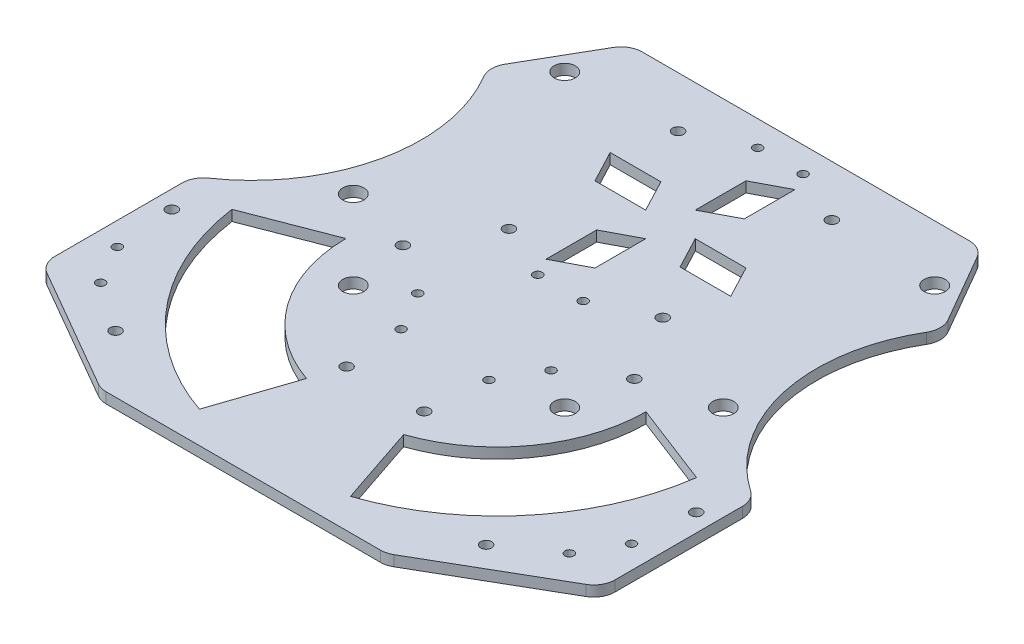
SolidWorks part; units mm, degrees
ref_plane "前视基准面" through (0, 0, 0) normal (0, 0, 1) x (1, 0, 0)
ref_plane "上视基准面" through (0, 0, 0) normal (0, 1, 0) x (1, 0, 0)
ref_plane "右视基准面" through (0, 0, 0) normal (1, 0, 0) x (0, 0, -1)
sketch "草图1" plane through (0, 0, 0) normal (0, 1, 0) x (1, 0, 0)
  line L0 (0, 0) -> (0, 50000) construction
  line L1 (0, 0) -> (-43301.2702, 25000) construction
  line L2 (-0.5416, -0.3127) -> (43300.7286, 24999.6873) construction
  line L3 (-34.641, 150) -> (-147.2243, -45)
  line L4 (34.641, 150) -> (147.2243, -45)
  line L5 (112.5833, -105) -> (-112.5833, -105)
  arc A0 (34.641, 150) -> (-34.641, 150) centre (0, 130) ccw
  arc A1 (-147.2243, -45) -> (-112.5833, -105) centre (-112.5833, -65) ccw
  arc A3 (147.2243, -45) -> (112.5833, -105) centre (112.5833, -65) cw
  dimension "D6" = 80
  dimension "D1" = 60
  dimension "D2" = 60
  dimension "D3" = 130
  dimension "D5" = 130
extrude "凸台-拉伸1" add sketch "草图1" along normal blind 5
sketch "草图2" plane through (0, 5, 0) normal (0, 1, 0) x (1, 0, 0)
  line L0 (0, 0) -> (0, 50000) construction
  line L1 (-10.75, 134) -> (-10.75, 30) construction
  line L2 (-10.75, 82) -> (49989.25, 82) construction
  circle A0 centre (-10.75, 30) radius 2.1
  circle A1 centre (-10.75, 134) radius 2.1
  circle A2 centre (10.75, 30) radius 2.1
  circle A3 centre (10.75, 134) radius 2.1
  circle A4 centre (-36.38, 42) radius 2.6
  circle A5 centre (-36.38, 122) radius 2.6
  circle A6 centre (36.38, 122) radius 2.6
  circle A7 centre (36.38, 42) radius 2.6
  point P15 (-10.75, 82)
  dimension "D1" = 4.2
  dimension "D6" = 5.2
  dimension "D2" = 21.5
  dimension "D3" = 104
  dimension "D4" = 30
  dimension "D5" = 80
  dimension "D7" = 36.38
extrude "切除-拉伸1" cut sketch "草图2" against normal blind 10
pattern_circular "阵列(圆周)1" count 3 over 360 about axis through (0, 0, 0.2137) along (0, 1, 0) of "切除-拉伸1"
sketch "草图3" plane through (0, 5, 0) normal (0, 1, 0) x (1, 0, 0)
  line L0 (-72.7463, -90) -> (72.7463, -90)
  line L1 (73.8956, -82.1687) -> (1.1494, -60.3448)
  line L2 (-1.1494, -60.3448) -> (-73.8956, -82.1687)
  line L3 (0, 0) -> (0, 50000) construction
  line L4 (-51.6854, 31.1678) -> (-34.2124, 105.0799)
  line L5 (-41.5692, 108.0001) -> (-114.3154, -18.0001)
  line L6 (-108.108, -22.9112) -> (-52.8348, 29.177)
  line L7 (52.8348, 29.177) -> (108.108, -22.9112)
  line L8 (114.3154, -18.0001) -> (41.5692, 108.0001)
  line L9 (34.2124, 105.0799) -> (51.6854, 31.1678)
  arc A0 (52.8348, 29.177) -> (51.6854, 31.1678) centre (55.5782, 32.0881) cw
  arc A1 (114.3154, -18.0001) -> (108.108, -22.9112) centre (110.8513, -20.0001) cw
  arc A2 (41.5692, 108.0001) -> (34.2124, 105.0799) centre (38.1051, 106.0001) ccw
  arc A3 (1.1494, -60.3448) -> (-1.1494, -60.3448) centre (0, -64.1761) ccw
  arc A4 (72.7463, -90) -> (73.8956, -82.1687) centre (72.7463, -86) ccw
  arc A5 (-72.7463, -90) -> (-73.8956, -82.1687) centre (-72.7463, -86) cw
  arc A6 (-108.108, -22.9112) -> (-114.3154, -18.0001) centre (-110.8513, -20.0001) cw
  arc A7 (-34.2124, 105.0799) -> (-41.5692, 108.0001) centre (-38.1051, 106.0001) ccw
  arc A8 (-51.6854, 31.1678) -> (-52.8348, 29.177) centre (-55.5782, 32.0881) cw
  point P15 (0, 0)
  point P23 (0, -60)
  point P26 (100, -90)
  point P29 (-100, -90)
  dimension "D1" = 200
  dimension "D5" = 4
  dimension "D2" = 30
  dimension "D3" = 60
  dimension "D4" = 3
sketch "草图4" plane through (0, 5, 0) normal (0, 1, 0) x (1, 0, 0)
  line L0 (0, 0) -> (0, 50000) construction
  line L5 (-6.3119, 115) -> (6.3119, 115)
  line L6 (8.2276, 112.4253) -> (0.9578, 88.1928)
  line L7 (-0.9578, 88.1928) -> (-8.2276, 112.4253)
  line L8 (-10.75, 30) -> (-10.75, 134) construction
  line L9 (-10.75, 82) -> (49989.25, 82) construction
  line L10 (8.2276, 51.5747) -> (0.9578, 75.8072)
  line L11 (-6.3119, 49) -> (6.3119, 49)
  line L12 (-0.9578, 75.8072) -> (-8.2276, 51.5747)
  line L13 (-10.75, 102.6866) -> (-10.75, 61.3134)
  line L14 (-8.7922, 61.0261) -> (-2.931, 80.5633)
  line L15 (-8.7922, 102.9739) -> (-2.931, 83.4367)
  line L16 (10.75, 102.6866) -> (10.75, 61.3134)
  line L17 (8.7922, 61.0261) -> (2.931, 80.5633)
  line L18 (8.7922, 102.9739) -> (2.931, 83.4367)
  line L19 (93.5741, -43.8727) -> (73.7238, -39.18)
  line L20 (57.2462, -22.8988) -> (71.2353, -37.7433)
  line L21 (94.3042, -42.0335) -> (58.474, -21.3469)
  line L22 (40.5512, -32.9127) -> (65.1721, -38.7331)
  line L23 (66.1299, -37.0741) -> (48.7788, -18.662)
  line L24 (45.5912, -19.0337) -> (39.2793, -29.9663)
  line L25 (83.5542, -60.6531) -> (47.724, -39.9665)
  line L26 (48.4541, -38.1273) -> (68.3043, -42.82)
  line L27 (84.7819, -59.1012) -> (70.7928, -44.2567)
  line L28 (76.8561, -43.2669) -> (101.477, -49.0873)
  line L29 (102.7489, -52.0337) -> (96.437, -62.9663)
  line L30 (93.2494, -63.338) -> (75.8983, -44.9259)
  line L31 (-84.7819, -59.1012) -> (-70.7928, -44.2567)
  line L32 (-48.4541, -38.1273) -> (-68.3043, -42.82)
  line L33 (-83.5542, -60.6531) -> (-47.724, -39.9665)
  line L34 (-48.7788, -18.662) -> (-66.1299, -37.0741)
  line L35 (-65.1721, -38.7331) -> (-40.5512, -32.9127)
  line L36 (-39.2793, -29.9663) -> (-45.5912, -19.0337)
  line L37 (-94.3042, -42.0335) -> (-58.474, -21.3469)
  line L38 (-57.2462, -22.8988) -> (-71.2353, -37.7433)
  line L39 (-93.5741, -43.8727) -> (-73.7238, -39.18)
  line L40 (-75.8983, -44.9259) -> (-93.2494, -63.338)
  line L41 (-96.437, -62.9663) -> (-102.7489, -52.0337)
  line L42 (-101.477, -49.0873) -> (-76.8561, -43.2669)
  arc A0 (2.931, 80.5633) -> (2.931, 83.4367) centre (7.7202, 82) cw
  arc A1 (-2.931, 80.5633) -> (-2.931, 83.4367) centre (-7.7202, 82) ccw
  arc A2 (-10.75, 61.3134) -> (-8.7922, 61.0261) centre (-9.75, 61.3134) ccw
  arc A3 (-8.7922, 102.9739) -> (-10.75, 102.6866) centre (-9.75, 102.6866) ccw
  arc A4 (10.75, 61.3134) -> (8.7922, 61.0261) centre (9.75, 61.3134) cw
  arc A5 (10.75, 102.6866) -> (8.7922, 102.9739) centre (9.75, 102.6866) ccw
  arc A6 (0.9578, 75.8072) -> (-0.9578, 75.8072) centre (0, 75.5199) ccw
  arc A7 (0.9578, 88.1928) -> (-0.9578, 88.1928) centre (0, 88.4801) cw
  arc A8 (6.3119, 49) -> (8.2276, 51.5747) centre (6.3119, 51) ccw
  arc A9 (-6.3119, 49) -> (-8.2276, 51.5747) centre (-6.3119, 51) cw
  arc A10 (8.2276, 112.4253) -> (6.3119, 115) centre (6.3119, 113) ccw
  arc A11 (-8.2276, 112.4253) -> (-6.3119, 115) centre (-6.3119, 113) cw
  arc A12 (93.5741, -43.8727) -> (94.3042, -42.0335) centre (93.8042, -42.8995) ccw
  arc A13 (71.2353, -37.7433) -> (73.7238, -39.18) centre (74.8742, -34.3142) ccw
  arc A14 (58.474, -21.3469) -> (57.2462, -22.8988) centre (57.974, -22.213) ccw
  arc A15 (39.2793, -29.9663) -> (40.5512, -32.9127) centre (41.0113, -30.9663) ccw
  arc A16 (65.1721, -38.7331) -> (66.1299, -37.0741) centre (65.4022, -37.7599) ccw
  arc A17 (45.5912, -19.0337) -> (48.7788, -18.662) centre (47.3233, -20.0337) cw
  arc A18 (83.5542, -60.6531) -> (84.7819, -59.1012) centre (84.0542, -59.787) ccw
  arc A19 (47.724, -39.9665) -> (48.4541, -38.1273) centre (48.224, -39.1005) cw
  arc A20 (68.3043, -42.82) -> (70.7928, -44.2567) centre (67.154, -47.6858) cw
  arc A21 (101.477, -49.0873) -> (102.7489, -52.0337) centre (101.0168, -51.0337) cw
  arc A22 (75.8983, -44.9259) -> (76.8561, -43.2669) centre (76.626, -44.2401) cw
  arc A23 (93.2494, -63.338) -> (96.437, -62.9663) centre (94.7049, -61.9663) ccw
  arc A24 (-84.7819, -59.1012) -> (-83.5542, -60.6531) centre (-84.0542, -59.787) ccw
  arc A25 (-68.3043, -42.82) -> (-70.7928, -44.2567) centre (-67.154, -47.6858) ccw
  arc A26 (-47.724, -39.9665) -> (-48.4541, -38.1273) centre (-48.224, -39.1005) ccw
  arc A27 (-45.5912, -19.0337) -> (-48.7788, -18.662) centre (-47.3233, -20.0337) ccw
  arc A28 (-66.1299, -37.0741) -> (-65.1721, -38.7331) centre (-65.4022, -37.7599) ccw
  arc A29 (-39.2793, -29.9663) -> (-40.5512, -32.9127) centre (-41.0113, -30.9663) cw
  arc A30 (-94.3042, -42.0335) -> (-93.5741, -43.8727) centre (-93.8042, -42.8995) ccw
  arc A31 (-58.474, -21.3469) -> (-57.2462, -22.8988) centre (-57.974, -22.213) cw
  arc A32 (-71.2353, -37.7433) -> (-73.7238, -39.18) centre (-74.8742, -34.3142) cw
  arc A33 (-93.2494, -63.338) -> (-96.437, -62.9663) centre (-94.7049, -61.9663) cw
  arc A34 (-76.8561, -43.2669) -> (-75.8983, -44.9259) centre (-76.626, -44.2401) cw
  arc A35 (-101.477, -49.0873) -> (-102.7489, -52.0337) centre (-101.0168, -51.0337) ccw
  point P11 (-10.75, 82)
  point P25 (2.5, 82)
  point P28 (-2.5, 82)
  point P31 (-10.75, 54.5)
  point P34 (-10.75, 109.5)
  point P37 (10.75, 54.5)
  point P40 (10.75, 109.5)
  point P43 (0, 79)
  point P46 (0, 85)
  point P49 (9, 49)
  point P52 (-9, 49)
  point P55 (9, 115)
  point P58 (-9, 115)
  point P133 (0, 0)
  dimension "D5" = 5
  dimension "D6" = 1
  dimension "D7" = 2
  dimension "D1" = 30
  dimension "D2" = 3
  dimension "D3" = 18
  dimension "D4" = 55
  dimension "D8" = 3
sketch "草图5" plane through (0, 0, 0) normal (0, -1, 0) x (1, 0, 0)
  line L15 (-147.2243, 45) -> (-34.641, -150)
  line L16 (-112.5833, 105) -> (112.5833, 105)
  line L17 (147.2243, 45) -> (34.641, -150)
  line L18 (69.282, -170) -> (181.8653, 25)
  line L19 (112.5833, 145) -> (-112.5833, 145)
  line L20 (-181.8653, 25) -> (-69.282, -170)
  line L21 (69.282, -170) -> (181.8653, 25)
  line L22 (112.5833, 145) -> (-112.5833, 145)
  line L23 (-181.8653, 25) -> (-69.282, -170)
  arc A11 (-112.5833, 105) -> (-147.2243, 45) centre (-112.5833, 65) ccw
  arc A12 (112.5833, 105) -> (147.2243, 45) centre (112.5833, 65) cw
  arc A13 (34.641, -150) -> (-34.641, -150) centre (0, -130) cw
  arc A14 (-69.282, -170) -> (69.282, -170) centre (0, -130) ccw
  arc A15 (181.8653, 25) -> (112.5833, 145) centre (112.5833, 65) ccw
  arc A16 (-112.5833, 145) -> (-181.8653, 25) centre (-112.5833, 65) ccw
  arc A17 (-69.282, -170) -> (69.282, -170) centre (0, -130) ccw
  arc A18 (181.8653, 25) -> (112.5833, 145) centre (112.5833, 65) ccw
  arc A19 (-112.5833, 145) -> (-181.8653, 25) centre (-112.5833, 65) ccw
  dimension "D1" = 40
extrude "凸台-拉伸3" add sketch "草图5" against normal blind 5
sketch "草图6" plane through (0, 5, 0) normal (0, 1, 0) x (1, 0, 0)
  line L0 (-87.5, 157) -> (87.5, 157) construction
  line L1 (-100, 169.5) -> (100, 169.5) construction
  line L2 (-100, 169.5) -> (-100, -30.5) construction
  line L3 (-100, -30.5) -> (100, -30.5) construction
  line L4 (100, 169.5) -> (100, -30.5) construction
  line L5 (-100, 169.5) -> (100, -30.5) construction
  line L6 (-100, -30.5) -> (100, 169.5) construction
  line L7 (87.5, 157) -> (87.5, -18) construction
  line L8 (-87.5, -18) -> (87.5, -18) construction
  line L9 (-87.5, 157) -> (-87.5, -18) construction
  line L10 (0, 157) -> (0, -18) construction
  line L11 (-87.5, 69.5) -> (87.5, 69.5) construction
  circle A0 centre (-87.5, 119.5) radius 5
  circle A1 centre (-87.5, 19.5) radius 5
  circle A2 centre (87.5, 19.5) radius 5
  circle A3 centre (87.5, 119.5) radius 5
  circle A7 centre (-50, -18) radius 5
  circle A8 centre (50, -18) radius 5
  point P0 (0, 33.5807)
  point P14 (-87.5, 69.5)
  dimension "D4" = 50
  dimension "D5" = 10
  dimension "D6" = 10
  dimension "D8" = 10
  dimension "D9" = 50
  dimension "D11" = 18
  dimension "D12" = 10
  dimension "D1" = 200
  dimension "D2" = 200
  dimension "D3" = 12.5
  dimension "D7" = 50
  dimension "D10" = 50
extrude "切除-拉伸2" cut sketch "草图6" against normal through all
sketch "草图8" plane through (0, 5, 0) normal (0, 1, 0) x (1, 0, 0)
  line L0 (-83.1384, 146) -> (83.1384, 146)
  line L1 (-181.8653, -25) -> (-69.282, 170) construction
  line L2 (69.282, 170) -> (181.8653, -25) construction
  line L3 (-83.1384, 146) -> (-69.282, 170)
  line L4 (69.282, 170) -> (83.1384, 146)
  arc A1 (69.282, 170) -> (-69.282, 170) centre (0, 130) ccw construction
  arc A2 (-69.282, 170) -> (69.282, 170) centre (0, 130) cw
  point P11 (0, 210)
  dimension "D1" = 64
extrude "切除-拉伸4" cut sketch "草图8" against normal through all
sketch "草图9" plane through (0, 5, 0) normal (0, 1, 0) x (1, 0, 0)
  line L0 (-132.5019, 60.5) -> (-132.5019, -82.5)
  line L1 (-181.8653, -25) -> (-83.1384, 146) construction
  line L2 (-132.5019, -82.5) -> (-67.55, -120)
  line L3 (-67.55, -120) -> (67.55, -120)
  line L4 (112.5833, -145) -> (-112.5833, -145) construction
  line L5 (0, -120) -> (0, 146) construction
  line L6 (-83.1384, 146) -> (83.1384, 146) construction
  line L7 (132.5019, -82.5) -> (67.55, -120)
  line L8 (132.5019, 60.5) -> (132.5019, -82.5)
  line L9 (-132.5019, 60.5) -> (-181.8653, -25)
  line L10 (-112.5833, -145) -> (112.5833, -145)
  line L11 (181.8653, -25) -> (132.5019, 60.5)
  arc A0 (-181.8653, -25) -> (-112.5833, -145) centre (-112.5833, -65) ccw
  arc A1 (112.5833, -145) -> (181.8653, -25) centre (112.5833, -65) ccw
  dimension "D1" = 120
  dimension "D2" = 150
  dimension "D3" = 25
  dimension "D4" = 75
extrude "切除-拉伸5" cut sketch "草图9" against normal through all contours L11 L8 L7 L3 L2 L0 L9 A0 L10 A1
sketch "草图10" plane through (0, 0, 0) normal (0, -1, 0) x (1, 0, 0)
  line L0 (-132.5019, -60.5) -> (-132.5019, 82.5) construction
  line L1 (-132.5019, -60.5) -> (-83.1384, -146) construction
  line L2 (132.5019, -60.5) -> (132.5019, 82.5) construction
  line L3 (83.1384, -146) -> (132.5019, -60.5) construction
  line L4 (-132.5019, 11) -> (-132.5019, -60.5)
  line L5 (-132.5019, -60.5) -> (-107.8202, -103.25)
  line L6 (132.5019, 11) -> (132.5019, -60.5)
  line L7 (132.5019, -60.5) -> (107.8202, -103.25)
  line L8 (0, -93.7597) -> (0, -117.7478)
  line L9 (0, -93.7597) -> (15.1924, -101.7557)
  line L10 (0, -117.7478) -> (15.1924, -125.7438)
  line L11 (15.1924, -101.7557) -> (15.1924, -125.7438)
  line L12 (-11.7275, -82.0322) -> (-35.7155, -82.0322)
  line L13 (-11.7275, -82.0322) -> (-19.7235, -97.2247)
  line L14 (-19.7235, -97.2247) -> (-43.7115, -97.2247)
  line L15 (-35.7155, -82.0322) -> (-43.7115, -97.2247)
  line L16 (0, -70.3048) -> (0, -46.3167)
  line L17 (0, -70.3048) -> (-15.1924, -62.3087)
  line L18 (-15.1924, -62.3087) -> (-15.1924, -38.3207)
  line L19 (0, -46.3167) -> (-15.1924, -38.3207)
  line L20 (11.7275, -82.0322) -> (35.7155, -82.0322)
  line L21 (11.7275, -82.0322) -> (19.7235, -66.8398)
  line L22 (19.7235, -66.8398) -> (43.7115, -66.8398)
  line L23 (35.7155, -82.0322) -> (43.7115, -66.8398)
  line L24 (0, 120) -> (0, 0) construction
  line L25 (-67.55, 120) -> (67.55, 120) construction
  line L26 (-109.8886, 15.5155) -> (-70.9767, 0.5146)
  line L27 (-35.7155, 105.0744) -> (-22.9758, 67.157)
  line L28 (109.8886, 15.5155) -> (70.9767, 0.5146)
  line L29 (35.7155, 105.0744) -> (22.9758, 67.157)
  arc A0 (-132.5019, 11) -> (-107.8202, -103.25) centre (-173.5592, -57.6607) cw
  arc A1 (132.5019, 11) -> (107.8202, -103.25) centre (173.5592, -57.6607) ccw
  arc A2 (-109.8886, 15.5155) -> (-35.7155, 105.0744) centre (0, 0) cw
  arc A3 (-70.9767, 0.5146) -> (-22.9758, 67.157) centre (0, 0) cw
  arc A4 (109.8886, 15.5155) -> (35.7155, 105.0744) centre (0, 0) ccw
  arc A5 (70.9767, 0.5146) -> (22.9758, 67.157) centre (0, 0) ccw
  point P10 (0, -82.0322)
  point P39 (0, -82.0322)
  dimension "D1" = 80
  dimension "D2" = 80
  dimension "D3" = 4
  dimension "D4" = 40
extrude "切除-拉伸6" cut sketch "草图10" against normal blind 10
fillet "圆角1" radius 10 4 edges at (-83.1384, 2.5, -146) (-107.8202, 2.5, -103.25) (-132.5019, 2.5, 11) (-132.5019, 2.5, 82.5)
fillet "圆角2" radius 10 6 edges at (-67.55, 2.5, 120) (67.55, 2.5, 120) (132.5019, 2.5, 82.5) (132.5019, 2.5, 11) (107.8202, 2.5, -103.25) (83.1384, 2.5, -146)
